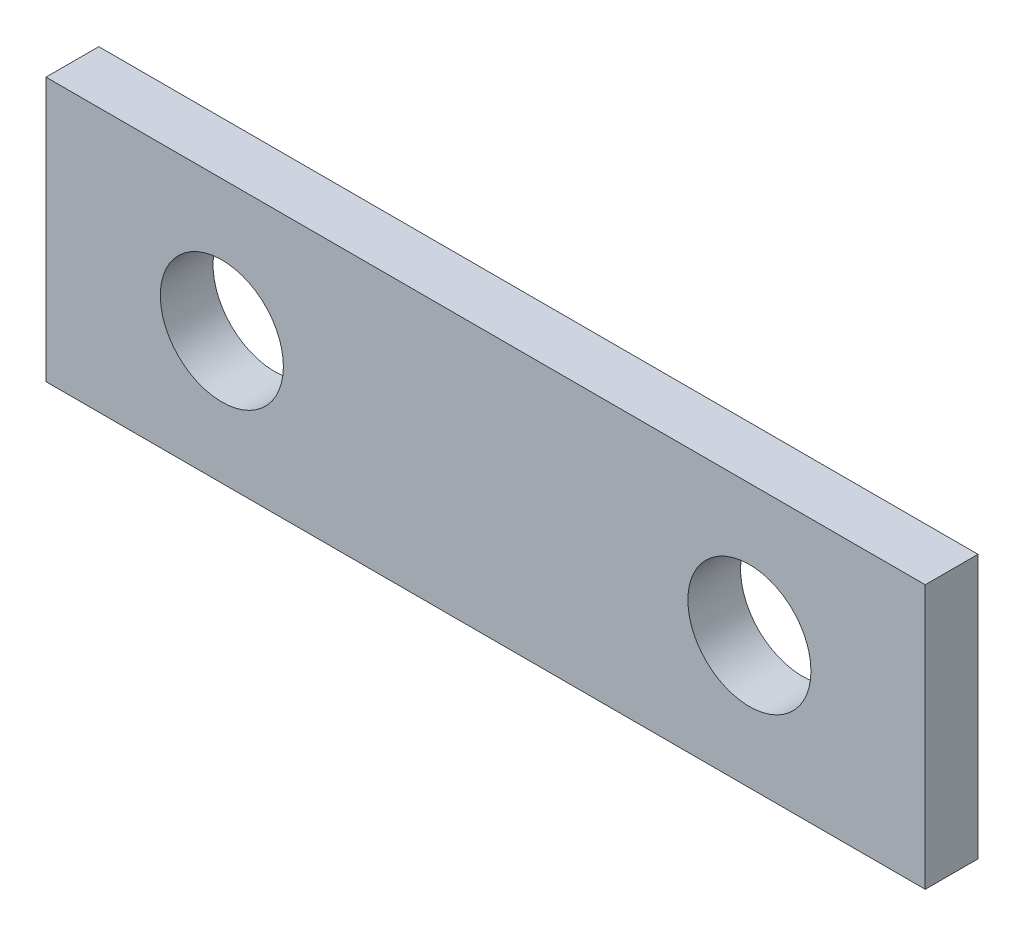
SolidWorks part; units mm, degrees
ref_plane "前视基准面" through (0, 0, 0) normal (0, 0, 1) x (1, 0, 0)
ref_plane "上视基准面" through (0, 0, 0) normal (0, 1, 0) x (1, 0, 0)
ref_plane "右视基准面" through (0, 0, 0) normal (1, 0, 0) x (0, 0, -1)
sketch "草图1" plane through (0, 0, 0) normal (0, 0, 1) x (1, 0, 0)
  line L0 (-1000, 15) -> (49000, 15) construction
  line L1 (0, 0) -> (100, 0)
  line L2 (0, 0) -> (0, 30)
  line L3 (0, 30) -> (100, 30)
  line L4 (100, 0) -> (100, 30)
  line L5 (50, -970) -> (50, 49030) construction
  circle A0 centre (20, 15) radius 7
  circle A1 centre (80, 15) radius 7
  point P8 (0, 15)
  point P11 (50, 30)
  dimension "D4" = 14
  dimension "D5" = 14
  dimension "D1" = 100
  dimension "D2" = 30
  dimension "D3" = 60
extrude "凸台-拉伸1" add sketch "草图1" along normal blind 6
